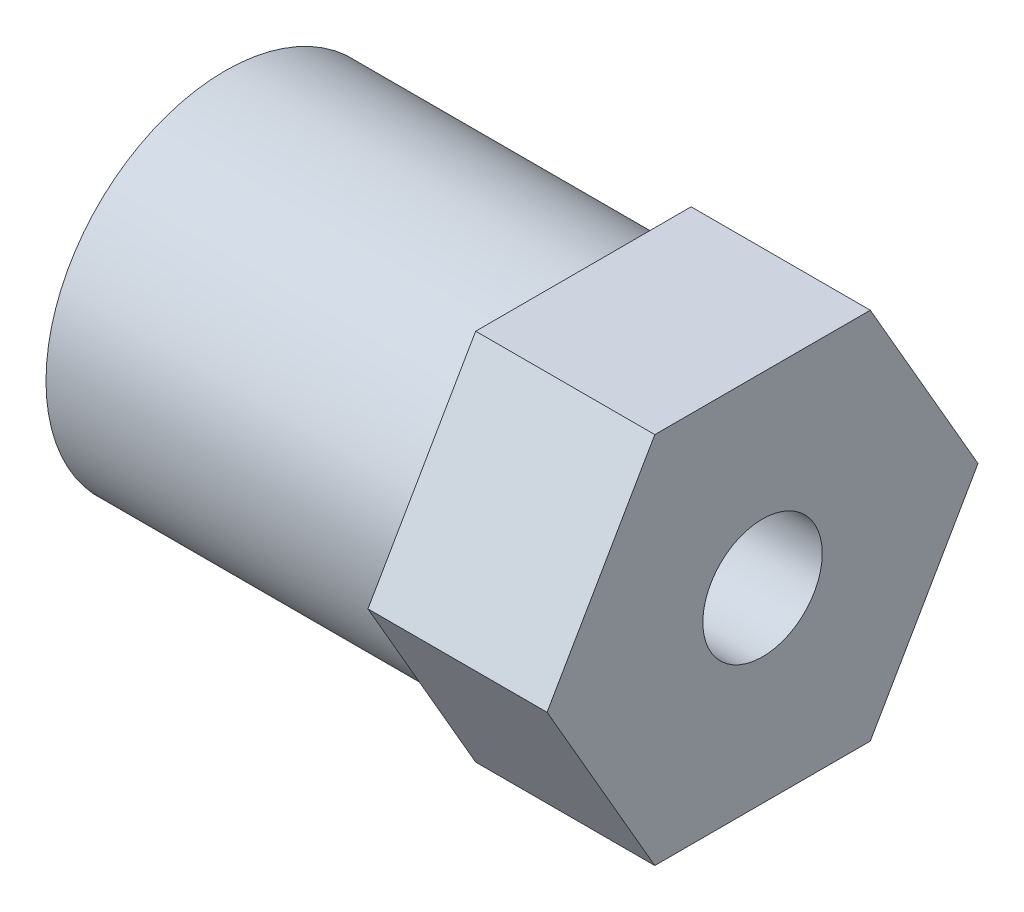
SolidWorks part; units mm, degrees
ref_plane "Front Plane" through (0, 0, 0) normal (0, 0, 1) x (1, 0, 0)
ref_plane "Top Plane" through (0, 0, 0) normal (0, 1, 0) x (1, 0, 0)
ref_plane "Right Plane" through (0, 0, 0) normal (1, 0, 0) x (0, 0, -1)
sketch "Sketch1" plane through (0, 0, 0) normal (1, 0, 0) x (0, 0, -1)
  line L1 (7.2169, 0) -> (3.6084, 6.25)
  line L2 (3.6084, 6.25) -> (-3.6084, 6.25)
  line L3 (-3.6084, 6.25) -> (-7.2169, 0)
  line L4 (-7.2169, 0) -> (-3.6084, -6.25)
  line L5 (-3.6084, -6.25) -> (3.6084, -6.25)
  line L6 (3.6084, -6.25) -> (7.2169, 0)
  circle A0 centre (0, 0) radius 6.25 construction
  dimension "D1" = 12.5
extrude "Boss-Extrude1" add sketch "Sketch1" along normal blind 6
sketch "Sketch2" plane through (0, 0, 0) normal (-1, 0, 0) x (0, 0, 1)
  circle A0 centre (0, 0) radius 6
  dimension "D1" = 12
extrude "Boss-Extrude2" add sketch "Sketch2" along normal blind 12
sketch "Sketch3" plane through (-12, 0, 0) normal (-1, 0, 0) x (0, 0, 1)
  circle A0 centre (0, 0) radius 3
  dimension "D1" = 6
extrude "Cut-Extrude1" cut sketch "Sketch3" against normal blind 12
sketch "Sketch4" plane through (6, 0, 0) normal (1, 0, 0) x (0, 0, -1)
  circle A0 centre (0, 0) radius 2
  dimension "D1" = 4
extrude "Cut-Extrude2" cut sketch "Sketch4" against normal through all
